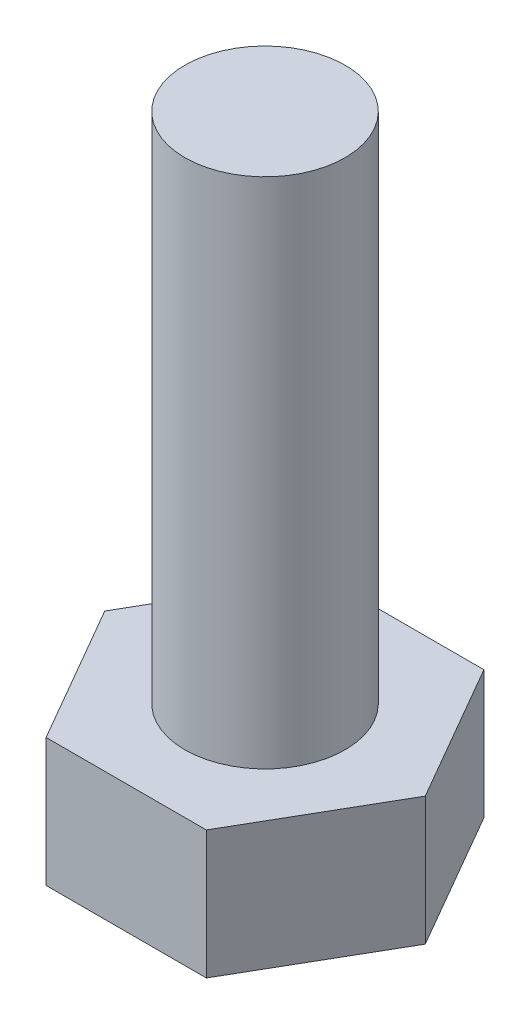
SolidWorks part; units mm, degrees
material "0.6020 (EN-GJL-200)"
ref_plane "前视基准面" through (0, 0, 0) normal (0, 0, 1) x (1, 0, 0)
ref_plane "上视基准面" through (0, 0, 0) normal (0, 1, 0) x (1, 0, 0)
ref_plane "右视基准面" through (0, 0, 0) normal (1, 0, 0) x (0, 0, -1)
other "Configuration Table"
sketch "草图1" plane through (0, 0, 0) normal (0, 1, 0) x (1, 0, 0)
  line L1 (1.25, 2.1651) -> (-1.25, 2.1651)
  line L2 (-1.25, 2.1651) -> (-2.5, 0)
  line L3 (-2.5, 0) -> (-1.25, -2.1651)
  line L4 (-1.25, -2.1651) -> (1.25, -2.1651)
  line L5 (1.25, -2.1651) -> (2.5, 0)
  line L6 (2.5, 0) -> (1.25, 2.1651)
  circle A0 centre (0, 0) radius 2.1651 construction
  dimension "D1" = 2.5
extrude "凸台-拉伸1" add sketch "草图1" along normal blind 2
sketch "草图2" plane through (0, 2, 0) normal (0, 1, 0) x (1, 0, 0)
  circle A0 centre (0, 0) radius 1.25
  dimension "D1" = 2.5
extrude "凸台-拉伸2" add sketch "草图2" along normal blind 8
